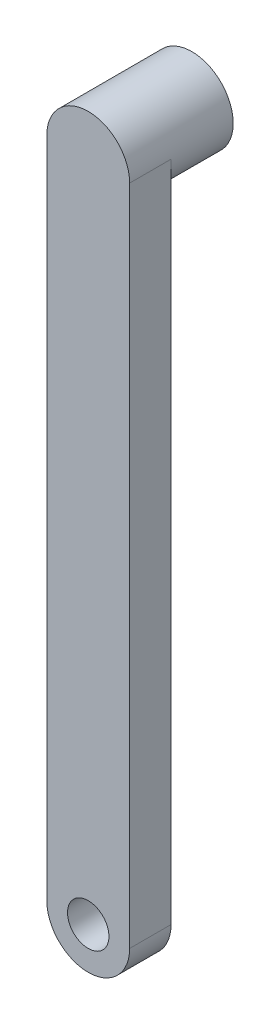
SolidWorks part; units mm, degrees
ref_plane "Plano frontal" through (0, 0, 0) normal (0, 0, 1) x (1, 0, 0)
ref_plane "Plano superior" through (0, 0, 0) normal (0, 1, 0) x (1, 0, 0)
ref_plane "Plano direito" through (0, 0, 0) normal (1, 0, 0) x (0, 0, -1)
sketch "Esboço1" plane through (0, 0, 0) normal (0, 0, 1) x (1, 0, 0)
  line L0 (-51.9394, 71.9646) -> (-51.9394, -88.0354)
  line L2 (-31.9394, -88.0354) -> (-31.9394, 71.9646)
  line L3 (-31.9394, 71.9646) -> (-51.9394, 71.9646)
  arc A0 (-51.9394, -88.0354) -> (-31.9394, -88.0354) centre (-41.9394, -88.0354) ccw
  dimension "D2" = 20
  dimension "D1" = 160
  dimension "D3" = 20
extrude "Ressalto-extrusão1" add sketch "Esboço1" along normal blind 10
sketch "Esboço2" plane through (0, 0, 10) normal (0, 0, 1) x (1, 0, 0)
  circle A0 centre (-41.9394, -88.0354) radius 5
  dimension "D1" = 10
extrude "Corte-extrusão1" cut sketch "Esboço2" against normal through all both and the other way through all
sketch "Esboço4" plane through (0, 0, 10) normal (0, 0, 1) x (1, 0, 0)
  line L0 (-31.9394, 71.9646) -> (-51.9394, 71.9646) construction
  circle A0 centre (-41.9394, 71.9646) radius 10
  dimension "D1" = 20
extrude "Ressalto-extrusão2" add sketch "Esboço4" against normal blind 25
